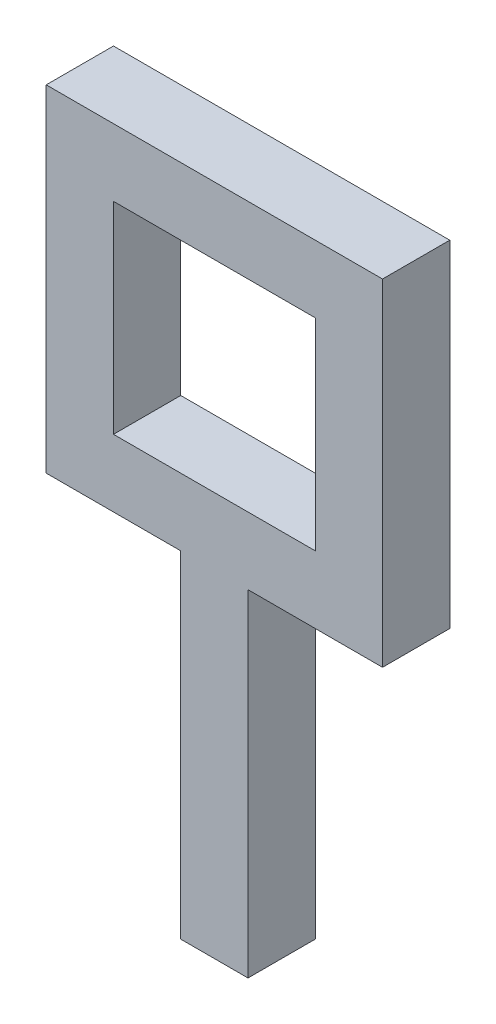
SolidWorks part; units mm, degrees
ref_plane "Plan de face" through (0, 0, 0) normal (0, 0, 1) x (1, 0, 0)
ref_plane "Plan de dessus" through (0, 0, 0) normal (0, 1, 0) x (1, 0, 0)
ref_plane "Plan de droite" through (0, 0, 0) normal (1, 0, 0) x (0, 0, -1)
sketch "Sketch1" plane through (0, 0, 0) normal (0, 1, 0) x (1, 0, 0)
  line L1 (1, -1) -> (-1, -1)
  line L2 (1, -1) -> (1, 1)
  line L3 (1, 1) -> (-1, 1)
  line L4 (-1, -1) -> (-1, 1)
  line L5 (1, -1) -> (-1, 1) construction
  line L6 (1, 1) -> (-1, -1) construction
  point P0 (0, 0)
  dimension "D1" = 2
  dimension "D2" = 2
extrude "Boss-Extrude1" add sketch "Sketch1" along normal blind 10
sketch "Sketch2" plane through (0, 10, 0) normal (0, 1, 0) x (-1, 0, 0)
  line L1 (-5, 1) -> (5, 1)
  line L2 (-5, 1) -> (-5, -1)
  line L3 (-5, -1) -> (5, -1)
  line L4 (5, 1) -> (5, -1)
  line L5 (-5, 1) -> (5, -1) construction
  line L6 (-5, -1) -> (5, 1) construction
  point P0 (0, 0)
  dimension "D1" = 10
  dimension "D2" = 2
extrude "Boss-Extrude2" add sketch "Sketch2" along normal blind 10
sketch "Sketch3" plane through (0, 0, 1) normal (0, 0, 1) x (1, 0, 0)
  line L1 (3, 12) -> (-3, 12)
  line L2 (3, 12) -> (3, 18)
  line L3 (3, 18) -> (-3, 18)
  line L4 (-3, 12) -> (-3, 18)
  line L5 (3, 12) -> (-3, 18) construction
  line L6 (3, 18) -> (-3, 12) construction
  line L8 (-5, 10) -> (-1, 10) construction
  line L9 (-5, 20) -> (-5, 10) construction
  point P0 (0, 15)
  point P7 (-3, 10)
  dimension "D1" = 2
  dimension "D2" = 2
  dimension "D3" = 6
  dimension "D4" = 6
extrude "Cut-Extrude1" cut sketch "Sketch3" against normal through all
